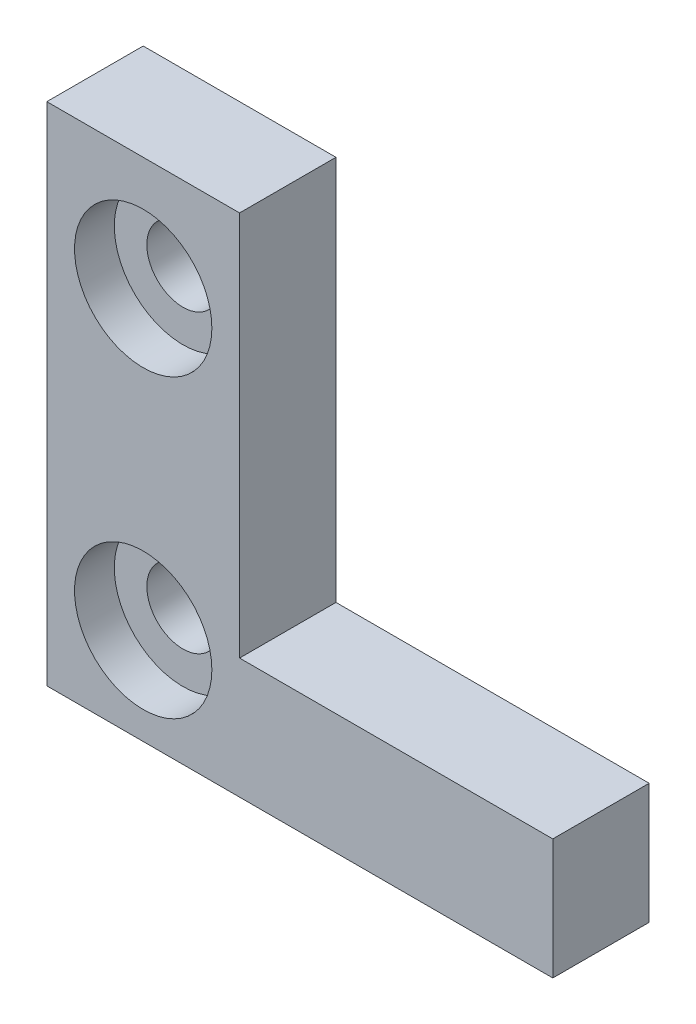
SolidWorks part; units mm, degrees
ref_plane "Alzado" through (0, 0, 0) normal (0, 0, 1) x (1, 0, 0)
ref_plane "Planta" through (0, 0, 0) normal (0, 1, 0) x (1, 0, 0)
ref_plane "Vista lateral" through (0, 0, 0) normal (1, 0, 0) x (0, 0, -1)
sketch "Croquis1" plane through (0, 0, 0) normal (0, 0, 1) x (1, 0, 0)
  line L1 (5, -75) -> (18, -75)
  line L2 (5, -75) -> (5, -83) construction
  line L3 (5, -83) -> (18, -83)
  line L4 (18, -75) -> (18, -83)
  line L8 (5, -83) -> (-3, -83)
  line L9 (5, -83) -> (5, -62)
  line L10 (5, -62) -> (-3, -62)
  line L11 (-3, -83) -> (-3, -62)
  line L12 (5, -83) -> (-3, -62) construction
  line L13 (5, -62) -> (-3, -83) construction
  circle A1 centre (1, -79) radius 1.5
  circle A2 centre (1, -66.715) radius 1.5
  point P4 (11.5, -79)
  point P11 (1, -72.5)
  dimension "D2" = 21
  dimension "D5" = 8
  dimension "D8" = 3
  dimension "D1" = 8
  dimension "D3" = 4
  dimension "D6" = 21
  dimension "D7" = 4
  dimension "D9" = 4.715
extrude "Saliente-Extruir1" add sketch "Croquis1" along normal blind 4
sketch "Croquis2" plane through (0, 0, 4) normal (0, 0, 1) x (1, 0, 0)
  circle A0 centre (1, -79) radius 2.85
  circle A1 centre (1, -66.715) radius 2.85
extrude "Cortar-Extruir1" cut sketch "Croquis2" against normal blind 1.65
sketch "Croquis3" plane through (18, 0, 0) normal (1, 0, 0) x (0, 0, -1)
  line L0 (0, -75) -> (0, -83) construction
  line L1 (-4, -75) -> (0, -75)
  line L2 (-4, -75) -> (-4, -78)
  line L3 (-4, -78) -> (0, -78)
  line L4 (0, -75) -> (0, -78)
  line L5 (-4, -75) -> (0, -78) construction
  line L6 (-4, -78) -> (0, -75) construction
  point P4 (-2, -76.5)
  dimension "D1" = 3
extrude "Cortar-Extruir2" cut sketch "Croquis3" against normal up to surface (13 mm away) up to face at (5, -68.5, 2)
